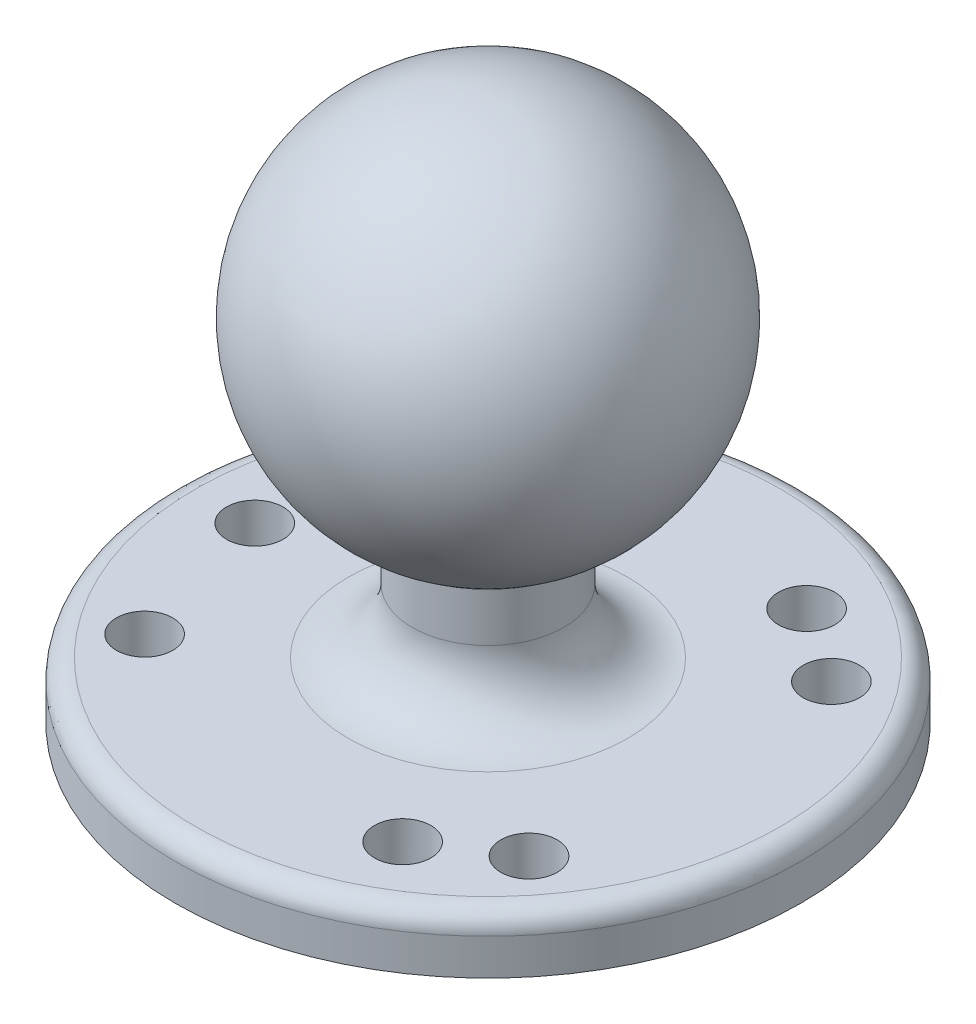
SolidWorks part; units mm, degrees
ref_plane "Front Plane" through (0, 0, 0) normal (0, 0, 1) x (1, 0, 0)
ref_plane "Top Plane" through (0, 0, 0) normal (0, 1, 0) x (1, 0, 0)
ref_plane "Right Plane" through (0, 0, 0) normal (1, 0, 0) x (0, 0, -1)
sketch "Sketch1" plane through (0, 0, 0) normal (0, 0, 1) x (1, 0, 0)
  line L0 (0, 0) -> (30.988, 0)
  line L1 (30.988, 0) -> (30.988, 3.588)
  line L2 (28.988, 5.588) -> (13.85, 5.588)
  line L3 (7.5, 11.938) -> (7.5, 17.2865)
  line L4 (0, 0) -> (0, 53.848) construction
  line L5 (0, 0) -> (0, 53.848)
  arc A0 (7.5, 17.2865) -> (0, 53.848) centre (0, 34.798) ccw
  arc A1 (28.988, 5.588) -> (30.988, 3.588) centre (28.988, 3.588) cw
  arc A2 (13.85, 5.588) -> (7.5, 11.938) centre (13.85, 11.938) cw
  point P9 (0, 34.798)
  point P10 (3.3063, 16.0371)
  point P11 (9.2632, 5.0737)
  point P16 (0, 0)
  dimension "D3" = 38.1
  dimension "D4" = 2
  dimension "D5" = 6.35
  dimension "D1" = 34.798
  dimension "D2" = 30.988
  dimension "D6" = 5.588
  dimension "D7" = 15
revolve "Revolve1" add sketch "Sketch1" angle 360 about L4
sketch "Sketch2" plane through (0, 0, 0) normal (0, -1, 0) x (1, 0, 0)
  line L0 (0, 0) -> (11.557, 20.0173) construction
  line L1 (0, 0) -> (11.557, -20.0173) construction
  line L2 (0, 0) -> (-23.114, 0) construction
  line L3 (-19.05, -14.986) -> (19.05, -14.986) construction
  circle A0 centre (0, 0) radius 23.114 construction
  circle A1 centre (-23.114, 0) radius 2.794
  circle A2 centre (11.557, 20.0173) radius 2.794
  circle A3 centre (11.557, -20.0173) radius 2.794
  circle A4 centre (-19.05, 14.986) radius 2.794
  circle A5 centre (19.05, 14.986) radius 2.794
  circle A6 centre (19.05, -14.986) radius 2.794
  circle A7 centre (-19.05, -14.986) radius 2.794
  point P11 (0, 0)
  point P18 (0, -14.986)
  point P19 (0, 0)
  point P20 (-19.05, -14.986)
  dimension "D1" = 5.588
  dimension "D8" = 5.588
  dimension "D3" = 23.114
  dimension "D4" = 120
  dimension "D5" = 38.1
  dimension "D6" = 14.986
  dimension "D7" = 29.972
  dimension "D2" = 3
extrude "Cut-Extrude1" cut sketch "Sketch2" against normal blind 10
